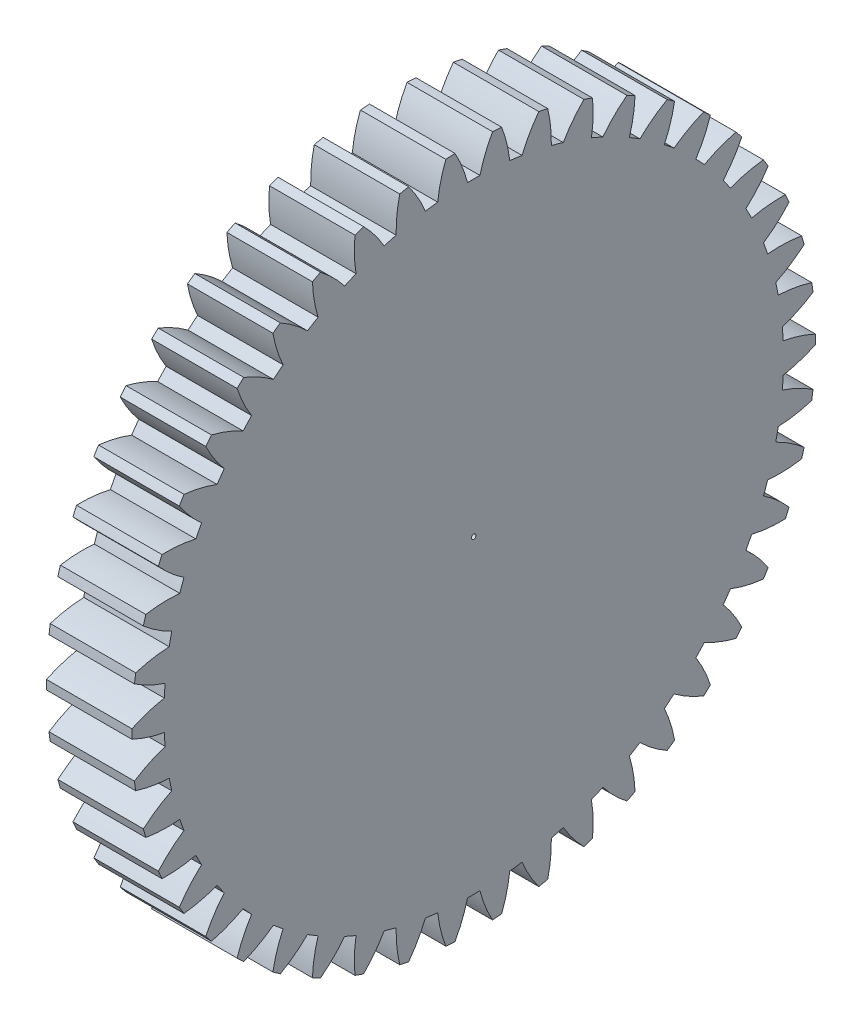
SolidWorks part; units mm, degrees
material "PLA "
ref_plane "Plane1" through (0, 0, 0) normal (0, 0, 1) x (1, 0, 0)
ref_plane "Plane2" through (0, 0, 0) normal (0, 1, 0) x (1, 0, 0)
ref_plane "Plane3" through (0, 0, 0) normal (1, 0, 0) x (0, 0, -1)
sketch "HoldingSke" plane through (0, 0, 0) normal (0, 1, 0) x (1, 0, 0)
  line L0 (0, 0) -> (0.2779, -0.2877)
  line L1 (-15, 0) -> (100, 0) construction
  line L2 (0, 0) -> (-2.1039, 2.3779)
  line L3 (0, 0) -> (-11.863, 4.5341)
  line L4 (0, 0) -> (5.9991, 6.2122)
  line L5 (0, 0) -> (-46.8476, -17.4728)
  line L6 (0, 0) -> (-9.9476, -6.7116)
  line L7 (-2.1039, 2.3779) -> (8.6586, 51.2059)
  line L8 (-76.2, 54.61) -> (-76.1, 54.61)
  line L9 (-71.009, 38.7566) -> (-53.1078, 45.2721)
  line L10 (-76.2, 71.12) -> (104.1128, 71.12)
  line L11 (0, 0) -> (-12, 0)
  line L12 (-76.2, 101.6) -> (-76.113, 101.6)
  line L13 (24.9733, 27.94) -> (52.9518, 28.4284)
  line L14 (24.9733, 27.94) -> (24.9743, 27.94)
  line L15 (24.9733, 27.94) -> (100.4006, 29.5858)
  line L16 (-63.627, -2.5) -> (-12.827, -2.5)
  circle A0 centre (0, 0) radius 0.4
  circle A1 centre (0, 0) radius 37.5
  circle A2 centre (0, 0) radius 37.5
  circle A3 centre (0, 0) radius 0.4
  dimension "MHD" = 75
  dimension "Hub_dia" = 75
  dimension "Bore" = 0.8
  dimension "MBD" = 0.8
  dimension "Num_teeth" = 46
  dimension "Pitch" = 0.4
  dimension "Overall_len" = 50
  dimension "Show_teeth" = 46
  dimension "Thickness" = 12
  dimension "OAL" = 50.0001
  dimension "T_dim" = 0.1
  dimension "Ap" = 20
  dimension "H" = 19.05
  dimension "Pitch_radius" = 180.3128
  dimension "Width" = 12
  dimension "Backlash" = 0.087
  dimension "Addendum_fac" = 1
  dimension "Dedendum_fac" = 1.25
  dimension "Clearance_fac" = 0.25
  dimension "Dedendum_add" = 0.001
  dimension "Module" = 2.5
sketch "BasProSke" plane through (0, 0, 0) normal (0, 1, 0) x (1, 0, 0)
  line L0 (-10, 0) -> (60, 0) construction
  line L1 (0, 0) -> (0, 60)
  line L2 (0, 0) -> (12, 0)
  line L3 (12, 0) -> (12, 60)
  line L4 (12, 60) -> (0, 60)
  dimension "Thickness" = 12
  dimension "Diameter" = 120
revolve "Base-Revolve" add sketch "BasProSke" angle 360 about L0
sketch "TooCutSke" plane through (0, 0, 0) normal (1, 0, 0) x (0, 0, -1)
  line L1 (0, 0) -> (0, 107) construction
  line L2 (0, 0) -> (-2.1154, 57.4611) construction
  line L3 (0, 0) -> (-7.844, 114.675) construction
  line L4 (-2.1154, 57.4611) -> (-3.922, 57.3375) construction
  arc A0 (1.091, 54.3631) -> (-1.091, 54.3631) centre (0, 0) ccw
  arc A1 (3.3102, 59.9341) -> (-3.3102, 59.9341) centre (0, 0) ccw
  circle A2 centre (0, 0) radius 57.5 construction
  circle A3 centre (0, 0) radius 54.0323 construction
  arc A4 (-1.091, 54.3631) -> (-3.3102, 59.9341) centre (-23.3853, 48.7095) ccw
  arc A5 (3.3102, 59.9341) -> (1.091, 54.3631) centre (23.3853, 48.7095) ccw
  dimension "Root_dia" = 108.748
  dimension "Overcut_dia" = 120.0508
  dimension "Pitch_dia" = 115
  dimension "Base_dia" = 108.0647
  dimension "Flank_rad" = 23
  dimension "Half_ang" = 3.913
  dimension "Half_CT" = 1.8109
extrude "ToothCut" cut sketch "TooCutSke" along normal through all
fillet "Breaks" [suppressed] radius 0.05
fillet "RootFillets" [suppressed] radius 0.626
pattern_circular "TeethCuts" count 46 over 360 about axis through (0, 0, 0) along (1, 0, 0) of "ToothCut", "RootFillets", "Breaks"
sketch "HubNeaOneSke" plane through (0, 0, 0) normal (-1, 0, 0) x (0, 0, 1)
  circle A0 centre (0, 0) radius 37.5
  dimension "Diameter" = 75
extrude "HubNearOne" [suppressed] add sketch "HubNeaOneSke" along normal blind 38.0001
sketch "HubNeaBotSke" plane through (0, 0, 0) normal (-1, 0, 0) x (0, 0, 1)
  circle A0 centre (0, 0) radius 37.5
  dimension "Diameter" = 75
extrude "HubNearBoth" [suppressed] add sketch "HubNeaBotSke" along normal blind 19
ref_plane "FarPln" through (12, 0, 0) normal (1, 0, 0) x (0, 0, -1)
sketch "HubFarSke" plane through (12, 0, 0) normal (1, 0, 0) x (0, 0, -1)
  circle A0 centre (0, 0) radius 37.5
  dimension "Diameter" = 75
extrude "HubFar" [suppressed] add sketch "HubFarSke" along normal blind 19
sketch "BorSke" plane through (0, 0, 0) normal (1, 0, 0) x (0, 0, -1)
  circle A0 centre (0, 0) radius 0.4
  dimension "Diameter" = 0.8
extrude "Bore" cut sketch "BorSke" along normal mid plane 100.0001
sketch "KeySke" plane through (0, 0, 0) normal (1, 0, 0) x (0, 0, -1)
  line L0 (-0.05, 0) -> (-0.05, 0.5)
  line L1 (-0.05, 0.5) -> (0.05, 0.5)
  line L2 (0.05, 0.5) -> (0.05, 0)
  line L3 (0, 0) -> (0, 34) construction
  line L4 (-0.05, 0) -> (0.05, 0)
  dimension "Offset" = 0.5
  dimension "Width" = 0.1
extrude "Keyway" [suppressed] cut sketch "KeySke" along normal mid plane 100.0001
pattern_circular "Keyway2" [suppressed] count 2 every 90 about axis through (-10, 0, 0) along (1, 0, 0)
sketch "Sketch1" plane through (12, 0, 0) normal (1, 0, 0) x (0, 0, -1)
  circle A0 centre (-0.4, 0) radius 22.4186
  circle A1 centre (0, 0) radius 0.4 construction
sketch "Sketch11" plane through (0, 0, 0) normal (0, 1, 0) x (1, 0, 0)
  circle A0 centre (12, 22.0186) radius 3.25
  dimension "D1" = 6.5
sketch "Sketch13" plane through (0, 0, 0) normal (-1, 0, 0) x (0, 0, 1)
  arc A184 (54.3108, -2.6215) -> (59.9947, -0.7996) centre (50.1919, 20.0067) ccw
  arc A185 (59.9947, -0.7996) -> (59.9947, 0.7996) centre (0, 0) ccw
  arc A186 (59.9947, 0.7996) -> (54.3108, 2.6215) centre (50.1919, -20.0067) ccw
  arc A187 (54.3108, 2.6215) -> (54.1619, 4.7983) centre (0, 0) ccw
  arc A188 (54.1619, 4.7983) -> (59.5448, 7.3771) centre (47.0001, 26.6548) ccw
  arc A189 (59.5448, 7.3771) -> (59.327, 8.9615) centre (0, 0) ccw
  arc A190 (59.327, 8.9615) -> (53.448, 9.9924) centre (52.4486, -12.9859) ccw
  arc A191 (53.448, 9.9924) -> (53.004, 12.1286) centre (0, 0) ccw
  arc A192 (53.004, 12.1286) -> (57.9856, 15.4164) centre (42.9329, 32.8064) ccw
  arc A193 (57.9856, 15.4164) -> (57.5542, 16.9564) centre (0, 0) ccw
  arc A194 (57.5542, 16.9564) -> (51.5895, 17.1771) centre (53.7284, -5.7232) ccw
  arc A195 (51.5895, 17.1771) -> (50.8588, 19.233) centre (0, 0) ccw
  arc A196 (50.8588, 19.233) -> (55.3464, 23.1685) centre (38.0658, 38.3469) ccw
  arc A197 (55.3464, 23.1685) -> (54.7092, 24.6354) centre (0, 0) ccw
  arc A198 (54.7092, 24.6354) -> (48.7701, 24.0419) centre (54.0072, 1.6461) ccw
  arc A199 (48.7701, 24.0419) -> (47.7662, 25.9792) centre (0, 0) ccw
  arc A200 (47.7662, 25.9792) -> (51.6761, 30.489) centre (32.4897, 43.173) ccw
  arc A201 (51.6761, 30.489) -> (50.8451, 31.8555) centre (0, 0) ccw
  arc A202 (50.8451, 31.8555) -> (45.0421, 30.4588) centre (53.2801, 8.9848) ccw
  arc A203 (45.0421, 30.4588) -> (43.7838, 32.2414) centre (0, 0) ccw
  arc A204 (43.7838, 32.2414) -> (47.0432, 37.2416) centre (26.3084, 47.1949) ccw
  arc A205 (47.0432, 37.2416) -> (46.0339, 38.4822) centre (0, 0) ccw
  arc A206 (46.0339, 38.4822) -> (40.4751, 36.3084) centre (51.5604, 16.156) ccw
  arc A207 (40.4751, 36.3084) -> (38.9858, 37.903) centre (0, 0) ccw
  arc A208 (38.9858, 37.903) -> (41.534, 43.3005) centre (19.637, 50.3377) ccw
  arc A209 (41.534, 43.3005) -> (40.3651, 44.3921) centre (0, 0) ccw
  arc A210 (40.3651, 44.3921) -> (35.1541, 41.4815) centre (48.8802, 23.0264) ccw
  arc A211 (35.1541, 41.4815) -> (33.4616, 42.8585) centre (0, 0) ccw
  arc A212 (33.4616, 42.8585) -> (35.251, 48.5527) centre (12.5998, 52.5427) ccw
  arc A213 (35.251, 48.5527) -> (33.9445, 49.475) centre (0, 0) ccw
  arc A214 (33.9445, 49.475) -> (29.1783, 45.882) centre (45.2896, 29.4678) ccw
  arc A215 (29.1783, 45.882) -> (27.314, 47.0157) centre (0, 0) ccw
  arc A216 (27.314, 47.0157) -> (28.3114, 52.9005) centre (5.3278, 53.769) ccw
  arc A217 (28.3114, 52.9005) -> (26.8915, 53.6363) centre (0, 0) ccw
  arc A218 (26.8915, 53.6363) -> (22.6589, 49.4278) centre (40.8552, 35.3602) ccw
  arc A219 (22.6589, 49.4278) -> (20.6577, 50.297) centre (0, 0) ccw
  arc A220 (20.6577, 50.297) -> (20.8445, 56.2629) centre (-2.0433, 53.9937) ccw
  arc A221 (20.8445, 56.2629) -> (19.3375, 56.7984) centre (0, 0) ccw
  arc A222 (19.3375, 56.7984) -> (15.7175, 52.0528) centre (35.6598, 40.594) ccw
  arc A223 (15.7175, 52.0528) -> (13.6165, 52.6415) centre (0, 0) ccw
  arc A224 (13.6165, 52.6415) -> (12.9892, 58.5771) centre (-9.3764, 53.2125) ccw
  arc A225 (12.9892, 58.5771) -> (11.4234, 58.9025) centre (0, 0) ccw
  arc A226 (11.4234, 58.9025) -> (8.4832, 53.7082) centre (29.8001, 45.0716) ccw
  arc A227 (8.4832, 53.7082) -> (6.3216, 54.0053) centre (0, 0) ccw
  arc A228 (6.3216, 54.0053) -> (4.892, 59.8002) centre (-16.5349, 51.4402) ccw
  arc A229 (4.892, 59.8002) -> (3.2964, 59.9094) centre (0, 0) ccw
  arc A230 (3.2964, 59.9094) -> (1.091, 54.3631) centre (23.3853, 48.7095) ccw
  arc A231 (1.091, 54.3631) -> (-1.091, 54.3631) centre (0, 0) ccw
  arc A232 (-1.091, 54.3631) -> (-3.2964, 59.9094) centre (-23.3853, 48.7095) ccw
  arc A233 (-3.2964, 59.9094) -> (-4.892, 59.8002) centre (0, 0) ccw
  arc A234 (-4.892, 59.8002) -> (-6.3216, 54.0053) centre (16.5349, 51.4402) ccw
  arc A235 (-6.3216, 54.0053) -> (-8.4832, 53.7082) centre (0, 0) ccw
  arc A236 (-8.4832, 53.7082) -> (-11.4234, 58.9025) centre (-29.8001, 45.0716) ccw
  arc A237 (-11.4234, 58.9025) -> (-12.9892, 58.5771) centre (0, 0) ccw
  arc A238 (-12.9892, 58.5771) -> (-13.6165, 52.6415) centre (9.3764, 53.2125) ccw
  arc A239 (-13.6165, 52.6415) -> (-15.7175, 52.0528) centre (0, 0) ccw
  arc A240 (-15.7175, 52.0528) -> (-19.3375, 56.7984) centre (-35.6598, 40.594) ccw
  arc A241 (-19.3375, 56.7984) -> (-20.8445, 56.2629) centre (0, 0) ccw
  arc A242 (-20.8445, 56.2629) -> (-20.6577, 50.297) centre (2.0433, 53.9937) ccw
  arc A243 (-20.6577, 50.297) -> (-22.6589, 49.4278) centre (0, 0) ccw
  arc A244 (-22.6589, 49.4278) -> (-26.8915, 53.6363) centre (-40.8552, 35.3602) ccw
  arc A245 (-26.8915, 53.6363) -> (-28.3114, 52.9005) centre (0, 0) ccw
  arc A246 (-28.3114, 52.9005) -> (-27.314, 47.0157) centre (-5.3278, 53.769) ccw
  arc A247 (-27.314, 47.0157) -> (-29.1783, 45.882) centre (0, 0) ccw
  arc A248 (-29.1783, 45.882) -> (-33.9445, 49.475) centre (-45.2896, 29.4678) ccw
  arc A249 (-33.9445, 49.475) -> (-35.251, 48.5527) centre (0, 0) ccw
  arc A250 (-35.251, 48.5527) -> (-33.4616, 42.8585) centre (-12.5998, 52.5427) ccw
  arc A251 (-33.4616, 42.8585) -> (-35.1541, 41.4815) centre (0, 0) ccw
  arc A252 (-35.1541, 41.4815) -> (-40.3651, 44.3921) centre (-48.8802, 23.0264) ccw
  arc A253 (-40.3651, 44.3921) -> (-41.534, 43.3005) centre (0, 0) ccw
  arc A254 (-41.534, 43.3005) -> (-38.9858, 37.903) centre (-19.637, 50.3377) ccw
  arc A255 (-38.9858, 37.903) -> (-40.4751, 36.3084) centre (0, 0) ccw
  arc A256 (-40.4751, 36.3084) -> (-46.0339, 38.4822) centre (-51.5604, 16.156) ccw
  arc A257 (-46.0339, 38.4822) -> (-47.0432, 37.2416) centre (0, 0) ccw
  arc A258 (-47.0432, 37.2416) -> (-43.7838, 32.2414) centre (-26.3084, 47.1949) ccw
  arc A259 (-43.7838, 32.2414) -> (-45.0421, 30.4588) centre (0, 0) ccw
  arc A260 (-45.0421, 30.4588) -> (-50.8451, 31.8555) centre (-53.2801, 8.9848) ccw
  arc A261 (-50.8451, 31.8555) -> (-51.6761, 30.489) centre (0, 0) ccw
  arc A262 (-51.6761, 30.489) -> (-47.7662, 25.9792) centre (-32.4897, 43.173) ccw
  arc A263 (-47.7662, 25.9792) -> (-48.7701, 24.0419) centre (0, 0) ccw
  arc A264 (-48.7701, 24.0419) -> (-54.7092, 24.6354) centre (-54.0072, 1.6461) ccw
  arc A265 (-54.7092, 24.6354) -> (-55.3464, 23.1685) centre (0, 0) ccw
  arc A266 (-55.3464, 23.1685) -> (-50.8588, 19.233) centre (-38.0658, 38.3469) ccw
  arc A267 (-50.8588, 19.233) -> (-51.5895, 17.1771) centre (0, 0) ccw
  arc A268 (-51.5895, 17.1771) -> (-57.5542, 16.9564) centre (-53.7284, -5.7232) ccw
  arc A269 (-57.5542, 16.9564) -> (-57.9856, 15.4164) centre (0, 0) ccw
  arc A270 (-57.9856, 15.4164) -> (-53.004, 12.1286) centre (-42.9329, 32.8064) ccw
  arc A271 (-53.004, 12.1286) -> (-53.448, 9.9924) centre (0, 0) ccw
  arc A272 (-53.448, 9.9924) -> (-59.327, 8.9615) centre (-52.4486, -12.9859) ccw
  arc A273 (-59.327, 8.9615) -> (-59.5448, 7.3771) centre (0, 0) ccw
  arc A274 (-59.5448, 7.3771) -> (-54.1619, 4.7983) centre (-47.0001, 26.6548) ccw
  arc A275 (-54.1619, 4.7983) -> (-54.3108, 2.6215) centre (0, 0) ccw
  arc A276 (-54.3108, 2.6215) -> (-59.9947, 0.7996) centre (-50.1919, -20.0067) ccw
  arc A277 (-59.9947, 0.7996) -> (-59.9947, -0.7996) centre (0, 0) ccw
  arc A278 (-59.9947, -0.7996) -> (-54.3108, -2.6215) centre (-50.1919, 20.0067) ccw
  arc A279 (-54.3108, -2.6215) -> (-54.1619, -4.7983) centre (0, 0) ccw
  arc A280 (-54.1619, -4.7983) -> (-59.5448, -7.3771) centre (-47.0001, -26.6548) ccw
  arc A281 (-59.5448, -7.3771) -> (-59.327, -8.9615) centre (0, 0) ccw
  arc A282 (-59.327, -8.9615) -> (-53.448, -9.9924) centre (-52.4486, 12.9859) ccw
  arc A283 (-53.448, -9.9924) -> (-53.004, -12.1286) centre (0, 0) ccw
  arc A284 (-53.004, -12.1286) -> (-57.9856, -15.4164) centre (-42.9329, -32.8064) ccw
  arc A285 (-57.9856, -15.4164) -> (-57.5542, -16.9564) centre (0, 0) ccw
  arc A286 (-57.5542, -16.9564) -> (-51.5895, -17.1771) centre (-53.7284, 5.7232) ccw
  arc A287 (-51.5895, -17.1771) -> (-50.8588, -19.233) centre (0, 0) ccw
  arc A288 (-50.8588, -19.233) -> (-55.3464, -23.1685) centre (-38.0658, -38.3469) ccw
  arc A289 (-55.3464, -23.1685) -> (-54.7092, -24.6354) centre (0, 0) ccw
  arc A290 (-54.7092, -24.6354) -> (-48.7701, -24.0419) centre (-54.0072, -1.6461) ccw
  arc A291 (-48.7701, -24.0419) -> (-47.7662, -25.9792) centre (0, 0) ccw
  arc A292 (-47.7662, -25.9792) -> (-51.6761, -30.489) centre (-32.4897, -43.173) ccw
  arc A293 (-51.6761, -30.489) -> (-50.8451, -31.8555) centre (0, 0) ccw
  arc A294 (-50.8451, -31.8555) -> (-45.0421, -30.4588) centre (-53.2801, -8.9848) ccw
  arc A295 (-45.0421, -30.4588) -> (-43.7838, -32.2414) centre (0, 0) ccw
  arc A296 (-43.7838, -32.2414) -> (-47.0432, -37.2416) centre (-26.3084, -47.1949) ccw
  arc A297 (-47.0432, -37.2416) -> (-46.0339, -38.4822) centre (0, 0) ccw
  arc A298 (-46.0339, -38.4822) -> (-40.4751, -36.3084) centre (-51.5604, -16.156) ccw
  arc A299 (-40.4751, -36.3084) -> (-38.9858, -37.903) centre (0, 0) ccw
  arc A300 (-38.9858, -37.903) -> (-41.534, -43.3005) centre (-19.637, -50.3377) ccw
  arc A301 (-41.534, -43.3005) -> (-40.3651, -44.3921) centre (0, 0) ccw
  arc A302 (-40.3651, -44.3921) -> (-35.1541, -41.4815) centre (-48.8802, -23.0264) ccw
  arc A303 (-35.1541, -41.4815) -> (-33.4616, -42.8585) centre (0, 0) ccw
  arc A304 (-33.4616, -42.8585) -> (-35.251, -48.5527) centre (-12.5998, -52.5427) ccw
  arc A305 (-35.251, -48.5527) -> (-33.9445, -49.475) centre (0, 0) ccw
  arc A306 (-33.9445, -49.475) -> (-29.1783, -45.882) centre (-45.2896, -29.4678) ccw
  arc A307 (-29.1783, -45.882) -> (-27.314, -47.0157) centre (0, 0) ccw
  arc A308 (-27.314, -47.0157) -> (-28.3114, -52.9005) centre (-5.3278, -53.769) ccw
  arc A309 (-28.3114, -52.9005) -> (-26.8915, -53.6363) centre (0, 0) ccw
  arc A310 (-26.8915, -53.6363) -> (-22.6589, -49.4278) centre (-40.8552, -35.3602) ccw
  arc A311 (-22.6589, -49.4278) -> (-20.6577, -50.297) centre (0, 0) ccw
  arc A312 (-20.6577, -50.297) -> (-20.8445, -56.2629) centre (2.0433, -53.9937) ccw
  arc A313 (-20.8445, -56.2629) -> (-19.3375, -56.7984) centre (0, 0) ccw
  arc A314 (-19.3375, -56.7984) -> (-15.7175, -52.0528) centre (-35.6598, -40.594) ccw
  arc A315 (-15.7175, -52.0528) -> (-13.6165, -52.6415) centre (0, 0) ccw
  arc A316 (-13.6165, -52.6415) -> (-12.9892, -58.5771) centre (9.3764, -53.2125) ccw
  arc A317 (-12.9892, -58.5771) -> (-11.4234, -58.9025) centre (0, 0) ccw
  arc A318 (-11.4234, -58.9025) -> (-8.4832, -53.7082) centre (-29.8001, -45.0716) ccw
  arc A319 (-8.4832, -53.7082) -> (-6.3216, -54.0053) centre (0, 0) ccw
  arc A320 (-6.3216, -54.0053) -> (-4.892, -59.8002) centre (16.5349, -51.4402) ccw
  arc A321 (-4.892, -59.8002) -> (-3.2964, -59.9094) centre (0, 0) ccw
  arc A322 (-3.2964, -59.9094) -> (-1.091, -54.3631) centre (-23.3853, -48.7095) ccw
  arc A323 (-1.091, -54.3631) -> (1.091, -54.3631) centre (0, 0) ccw
  arc A324 (1.091, -54.3631) -> (3.2964, -59.9094) centre (23.3853, -48.7095) ccw
  arc A325 (3.2964, -59.9094) -> (4.892, -59.8002) centre (0, 0) ccw
  arc A326 (4.892, -59.8002) -> (6.3216, -54.0053) centre (-16.5349, -51.4402) ccw
  arc A327 (6.3216, -54.0053) -> (8.4832, -53.7082) centre (0, 0) ccw
  arc A328 (8.4832, -53.7082) -> (11.4234, -58.9025) centre (29.8001, -45.0716) ccw
  arc A329 (11.4234, -58.9025) -> (12.9892, -58.5771) centre (0, 0) ccw
  arc A330 (12.9892, -58.5771) -> (13.6165, -52.6415) centre (-9.3764, -53.2125) ccw
  arc A331 (13.6165, -52.6415) -> (15.7175, -52.0528) centre (0, 0) ccw
  arc A332 (15.7175, -52.0528) -> (19.3375, -56.7984) centre (35.6598, -40.594) ccw
  arc A333 (19.3375, -56.7984) -> (20.8445, -56.2629) centre (0, 0) ccw
  arc A334 (20.8445, -56.2629) -> (20.6577, -50.297) centre (-2.0433, -53.9937) ccw
  arc A335 (20.6577, -50.297) -> (22.6589, -49.4278) centre (0, 0) ccw
  arc A336 (22.6589, -49.4278) -> (26.8915, -53.6363) centre (40.8552, -35.3602) ccw
  arc A337 (26.8915, -53.6363) -> (28.3114, -52.9005) centre (0, 0) ccw
  arc A338 (28.3114, -52.9005) -> (27.314, -47.0157) centre (5.3278, -53.769) ccw
  arc A339 (27.314, -47.0157) -> (29.1783, -45.882) centre (0, 0) ccw
  arc A340 (29.1783, -45.882) -> (33.9445, -49.475) centre (45.2896, -29.4678) ccw
  arc A341 (33.9445, -49.475) -> (35.251, -48.5527) centre (0, 0) ccw
  arc A342 (35.251, -48.5527) -> (33.4616, -42.8585) centre (12.5998, -52.5427) ccw
  arc A343 (33.4616, -42.8585) -> (35.1541, -41.4815) centre (0, 0) ccw
  arc A344 (35.1541, -41.4815) -> (40.3651, -44.3921) centre (48.8802, -23.0264) ccw
  arc A345 (40.3651, -44.3921) -> (41.534, -43.3005) centre (0, 0) ccw
  arc A346 (41.534, -43.3005) -> (38.9858, -37.903) centre (19.637, -50.3377) ccw
  arc A347 (38.9858, -37.903) -> (40.4751, -36.3084) centre (0, 0) ccw
  arc A348 (40.4751, -36.3084) -> (46.0339, -38.4822) centre (51.5604, -16.156) ccw
  arc A349 (46.0339, -38.4822) -> (47.0432, -37.2416) centre (0, 0) ccw
  arc A350 (47.0432, -37.2416) -> (43.7838, -32.2414) centre (26.3084, -47.1949) ccw
  arc A351 (43.7838, -32.2414) -> (45.0421, -30.4588) centre (0, 0) ccw
  arc A352 (45.0421, -30.4588) -> (50.8451, -31.8555) centre (53.2801, -8.9848) ccw
  arc A353 (50.8451, -31.8555) -> (51.6761, -30.489) centre (0, 0) ccw
  arc A354 (51.6761, -30.489) -> (47.7662, -25.9792) centre (32.4897, -43.173) ccw
  arc A355 (47.7662, -25.9792) -> (48.7701, -24.0419) centre (0, 0) ccw
  arc A356 (48.7701, -24.0419) -> (54.7092, -24.6354) centre (54.0072, -1.6461) ccw
  arc A357 (54.7092, -24.6354) -> (55.3464, -23.1685) centre (0, 0) ccw
  arc A358 (55.3464, -23.1685) -> (50.8588, -19.233) centre (38.0658, -38.3469) ccw
  arc A359 (50.8588, -19.233) -> (51.5895, -17.1771) centre (0, 0) ccw
  arc A360 (51.5895, -17.1771) -> (57.5542, -16.9564) centre (53.7284, 5.7232) ccw
  arc A361 (57.5542, -16.9564) -> (57.9856, -15.4164) centre (0, 0) ccw
  arc A362 (57.9856, -15.4164) -> (53.004, -12.1286) centre (42.9329, -32.8064) ccw
  arc A363 (53.004, -12.1286) -> (53.448, -9.9924) centre (0, 0) ccw
  arc A364 (53.448, -9.9924) -> (59.327, -8.9615) centre (52.4486, 12.9859) ccw
  arc A365 (59.327, -8.9615) -> (59.5448, -7.3771) centre (0, 0) ccw
  arc A366 (59.5448, -7.3771) -> (54.1619, -4.7983) centre (47.0001, -26.6548) ccw
  arc A367 (54.1619, -4.7983) -> (54.3108, -2.6215) centre (0, 0) ccw
  arc A368 (54.3108, -2.6215) -> (59.9947, -0.7996) centre (50.1919, 20.0067) ccw
  arc A369 (59.9947, -0.7996) -> (59.9947, 0.7996) centre (0, 0) ccw
  arc A370 (59.9947, 0.7996) -> (54.3108, 2.6215) centre (50.1919, -20.0067) ccw
  arc A371 (54.3108, 2.6215) -> (54.1619, 4.7983) centre (0, 0) ccw
  arc A372 (54.1619, 4.7983) -> (59.5448, 7.3771) centre (47.0001, 26.6548) ccw
  arc A373 (59.5448, 7.3771) -> (59.327, 8.9615) centre (0, 0) ccw
  arc A374 (59.327, 8.9615) -> (53.448, 9.9924) centre (52.4486, -12.9859) ccw
  arc A375 (53.448, 9.9924) -> (53.004, 12.1286) centre (0, 0) ccw
  arc A376 (53.004, 12.1286) -> (57.9856, 15.4164) centre (42.9329, 32.8064) ccw
  arc A377 (57.9856, 15.4164) -> (57.5542, 16.9564) centre (0, 0) ccw
  arc A378 (57.5542, 16.9564) -> (51.5895, 17.1771) centre (53.7284, -5.7232) ccw
  arc A379 (51.5895, 17.1771) -> (50.8588, 19.233) centre (0, 0) ccw
  arc A380 (50.8588, 19.233) -> (55.3464, 23.1685) centre (38.0658, 38.3469) ccw
  arc A381 (55.3464, 23.1685) -> (54.7092, 24.6354) centre (0, 0) ccw
  arc A382 (54.7092, 24.6354) -> (48.7701, 24.0419) centre (54.0072, 1.6461) ccw
  arc A383 (48.7701, 24.0419) -> (47.7662, 25.9792) centre (0, 0) ccw
  arc A384 (47.7662, 25.9792) -> (51.6761, 30.489) centre (32.4897, 43.173) ccw
  arc A385 (51.6761, 30.489) -> (50.8451, 31.8555) centre (0, 0) ccw
  arc A386 (50.8451, 31.8555) -> (45.0421, 30.4588) centre (53.2801, 8.9848) ccw
  arc A387 (45.0421, 30.4588) -> (43.7838, 32.2414) centre (0, 0) ccw
  arc A388 (43.7838, 32.2414) -> (47.0432, 37.2416) centre (26.3084, 47.1949) ccw
  arc A389 (47.0432, 37.2416) -> (46.0339, 38.4822) centre (0, 0) ccw
  arc A390 (46.0339, 38.4822) -> (40.4751, 36.3084) centre (51.5604, 16.156) ccw
  arc A391 (40.4751, 36.3084) -> (38.9858, 37.903) centre (0, 0) ccw
  arc A392 (38.9858, 37.903) -> (41.534, 43.3005) centre (19.637, 50.3377) ccw
  arc A393 (41.534, 43.3005) -> (40.3651, 44.3921) centre (0, 0) ccw
  arc A394 (40.3651, 44.3921) -> (35.1541, 41.4815) centre (48.8802, 23.0264) ccw
  arc A395 (35.1541, 41.4815) -> (33.4616, 42.8585) centre (0, 0) ccw
  arc A396 (33.4616, 42.8585) -> (35.251, 48.5527) centre (12.5998, 52.5427) ccw
  arc A397 (35.251, 48.5527) -> (33.9445, 49.475) centre (0, 0) ccw
  arc A398 (33.9445, 49.475) -> (29.1783, 45.882) centre (45.2896, 29.4678) ccw
  arc A399 (29.1783, 45.882) -> (27.314, 47.0157) centre (0, 0) ccw
  arc A400 (27.314, 47.0157) -> (28.3114, 52.9005) centre (5.3278, 53.769) ccw
  arc A401 (28.3114, 52.9005) -> (26.8915, 53.6363) centre (0, 0) ccw
  arc A402 (26.8915, 53.6363) -> (22.6589, 49.4278) centre (40.8552, 35.3602) ccw
  arc A403 (22.6589, 49.4278) -> (20.6577, 50.297) centre (0, 0) ccw
  arc A404 (20.6577, 50.297) -> (20.8445, 56.2629) centre (-2.0433, 53.9937) ccw
  arc A405 (20.8445, 56.2629) -> (19.3375, 56.7984) centre (0, 0) ccw
  arc A406 (19.3375, 56.7984) -> (15.7175, 52.0528) centre (35.6598, 40.594) ccw
  arc A407 (15.7175, 52.0528) -> (13.6165, 52.6415) centre (0, 0) ccw
  arc A408 (13.6165, 52.6415) -> (12.9892, 58.5771) centre (-9.3764, 53.2125) ccw
  arc A409 (12.9892, 58.5771) -> (11.4234, 58.9025) centre (0, 0) ccw
  arc A410 (11.4234, 58.9025) -> (8.4832, 53.7082) centre (29.8001, 45.0716) ccw
  arc A411 (8.4832, 53.7082) -> (6.3216, 54.0053) centre (0, 0) ccw
  arc A412 (6.3216, 54.0053) -> (4.892, 59.8002) centre (-16.5349, 51.4402) ccw
  arc A413 (4.892, 59.8002) -> (3.2964, 59.9094) centre (0, 0) ccw
  arc A414 (3.2964, 59.9094) -> (1.091, 54.3631) centre (23.3853, 48.7095) ccw
  arc A415 (1.091, 54.3631) -> (-1.091, 54.3631) centre (0, 0) ccw
  arc A416 (-1.091, 54.3631) -> (-3.2964, 59.9094) centre (-23.3853, 48.7095) ccw
  arc A417 (-3.2964, 59.9094) -> (-4.892, 59.8002) centre (0, 0) ccw
  arc A418 (-4.892, 59.8002) -> (-6.3216, 54.0053) centre (16.5349, 51.4402) ccw
  arc A419 (-6.3216, 54.0053) -> (-8.4832, 53.7082) centre (0, 0) ccw
  arc A420 (-8.4832, 53.7082) -> (-11.4234, 58.9025) centre (-29.8001, 45.0716) ccw
  arc A421 (-11.4234, 58.9025) -> (-12.9892, 58.5771) centre (0, 0) ccw
  arc A422 (-12.9892, 58.5771) -> (-13.6165, 52.6415) centre (9.3764, 53.2125) ccw
  arc A423 (-13.6165, 52.6415) -> (-15.7175, 52.0528) centre (0, 0) ccw
  arc A424 (-15.7175, 52.0528) -> (-19.3375, 56.7984) centre (-35.6598, 40.594) ccw
  arc A425 (-19.3375, 56.7984) -> (-20.8445, 56.2629) centre (0, 0) ccw
  arc A426 (-20.8445, 56.2629) -> (-20.6577, 50.297) centre (2.0433, 53.9937) ccw
  arc A427 (-20.6577, 50.297) -> (-22.6589, 49.4278) centre (0, 0) ccw
  arc A428 (-22.6589, 49.4278) -> (-26.8915, 53.6363) centre (-40.8552, 35.3602) ccw
  arc A429 (-26.8915, 53.6363) -> (-28.3114, 52.9005) centre (0, 0) ccw
  arc A430 (-28.3114, 52.9005) -> (-27.314, 47.0157) centre (-5.3278, 53.769) ccw
  arc A431 (-27.314, 47.0157) -> (-29.1783, 45.882) centre (0, 0) ccw
  arc A432 (-29.1783, 45.882) -> (-33.9445, 49.475) centre (-45.2896, 29.4678) ccw
  arc A433 (-33.9445, 49.475) -> (-35.251, 48.5527) centre (0, 0) ccw
  arc A434 (-35.251, 48.5527) -> (-33.4616, 42.8585) centre (-12.5998, 52.5427) ccw
  arc A435 (-33.4616, 42.8585) -> (-35.1541, 41.4815) centre (0, 0) ccw
  arc A436 (-35.1541, 41.4815) -> (-40.3651, 44.3921) centre (-48.8802, 23.0264) ccw
  arc A437 (-40.3651, 44.3921) -> (-41.534, 43.3005) centre (0, 0) ccw
  arc A438 (-41.534, 43.3005) -> (-38.9858, 37.903) centre (-19.637, 50.3377) ccw
  arc A439 (-38.9858, 37.903) -> (-40.4751, 36.3084) centre (0, 0) ccw
  arc A440 (-40.4751, 36.3084) -> (-46.0339, 38.4822) centre (-51.5604, 16.156) ccw
  arc A441 (-46.0339, 38.4822) -> (-47.0432, 37.2416) centre (0, 0) ccw
  arc A442 (-47.0432, 37.2416) -> (-43.7838, 32.2414) centre (-26.3084, 47.1949) ccw
  arc A443 (-43.7838, 32.2414) -> (-45.0421, 30.4588) centre (0, 0) ccw
  arc A444 (-45.0421, 30.4588) -> (-50.8451, 31.8555) centre (-53.2801, 8.9848) ccw
  arc A445 (-50.8451, 31.8555) -> (-51.6761, 30.489) centre (0, 0) ccw
  arc A446 (-51.6761, 30.489) -> (-47.7662, 25.9792) centre (-32.4897, 43.173) ccw
  arc A447 (-47.7662, 25.9792) -> (-48.7701, 24.0419) centre (0, 0) ccw
  arc A448 (-48.7701, 24.0419) -> (-54.7092, 24.6354) centre (-54.0072, 1.6461) ccw
  arc A449 (-54.7092, 24.6354) -> (-55.3464, 23.1685) centre (0, 0) ccw
  arc A450 (-55.3464, 23.1685) -> (-50.8588, 19.233) centre (-38.0658, 38.3469) ccw
  arc A451 (-50.8588, 19.233) -> (-51.5895, 17.1771) centre (0, 0) ccw
  arc A452 (-51.5895, 17.1771) -> (-57.5542, 16.9564) centre (-53.7284, -5.7232) ccw
  arc A453 (-57.5542, 16.9564) -> (-57.9856, 15.4164) centre (0, 0) ccw
  arc A454 (-57.9856, 15.4164) -> (-53.004, 12.1286) centre (-42.9329, 32.8064) ccw
  arc A455 (-53.004, 12.1286) -> (-53.448, 9.9924) centre (0, 0) ccw
  arc A456 (-53.448, 9.9924) -> (-59.327, 8.9615) centre (-52.4486, -12.9859) ccw
  arc A457 (-59.327, 8.9615) -> (-59.5448, 7.3771) centre (0, 0) ccw
  arc A458 (-59.5448, 7.3771) -> (-54.1619, 4.7983) centre (-47.0001, 26.6548) ccw
  arc A459 (-54.1619, 4.7983) -> (-54.3108, 2.6215) centre (0, 0) ccw
  arc A460 (-54.3108, 2.6215) -> (-59.9947, 0.7996) centre (-50.1919, -20.0067) ccw
  arc A461 (-59.9947, 0.7996) -> (-59.9947, -0.7996) centre (0, 0) ccw
  arc A462 (-59.9947, -0.7996) -> (-54.3108, -2.6215) centre (-50.1919, 20.0067) ccw
  arc A463 (-54.3108, -2.6215) -> (-54.1619, -4.7983) centre (0, 0) ccw
  arc A464 (-54.1619, -4.7983) -> (-59.5448, -7.3771) centre (-47.0001, -26.6548) ccw
  arc A465 (-59.5448, -7.3771) -> (-59.327, -8.9615) centre (0, 0) ccw
  arc A466 (-59.327, -8.9615) -> (-53.448, -9.9924) centre (-52.4486, 12.9859) ccw
  arc A467 (-53.448, -9.9924) -> (-53.004, -12.1286) centre (0, 0) ccw
  arc A468 (-53.004, -12.1286) -> (-57.9856, -15.4164) centre (-42.9329, -32.8064) ccw
  arc A469 (-57.9856, -15.4164) -> (-57.5542, -16.9564) centre (0, 0) ccw
  arc A470 (-57.5542, -16.9564) -> (-51.5895, -17.1771) centre (-53.7284, 5.7232) ccw
  arc A471 (-51.5895, -17.1771) -> (-50.8588, -19.233) centre (0, 0) ccw
  arc A472 (-50.8588, -19.233) -> (-55.3464, -23.1685) centre (-38.0658, -38.3469) ccw
  arc A473 (-55.3464, -23.1685) -> (-54.7092, -24.6354) centre (0, 0) ccw
  arc A474 (-54.7092, -24.6354) -> (-48.7701, -24.0419) centre (-54.0072, -1.6461) ccw
  arc A475 (-48.7701, -24.0419) -> (-47.7662, -25.9792) centre (0, 0) ccw
  arc A476 (-47.7662, -25.9792) -> (-51.6761, -30.489) centre (-32.4897, -43.173) ccw
  arc A477 (-51.6761, -30.489) -> (-50.8451, -31.8555) centre (0, 0) ccw
  arc A478 (-50.8451, -31.8555) -> (-45.0421, -30.4588) centre (-53.2801, -8.9848) ccw
  arc A479 (-45.0421, -30.4588) -> (-43.7838, -32.2414) centre (0, 0) ccw
  arc A480 (-43.7838, -32.2414) -> (-47.0432, -37.2416) centre (-26.3084, -47.1949) ccw
  arc A481 (-47.0432, -37.2416) -> (-46.0339, -38.4822) centre (0, 0) ccw
  arc A482 (-46.0339, -38.4822) -> (-40.4751, -36.3084) centre (-51.5604, -16.156) ccw
  arc A483 (-40.4751, -36.3084) -> (-38.9858, -37.903) centre (0, 0) ccw
  arc A484 (-38.9858, -37.903) -> (-41.534, -43.3005) centre (-19.637, -50.3377) ccw
  arc A485 (-41.534, -43.3005) -> (-40.3651, -44.3921) centre (0, 0) ccw
  arc A486 (-40.3651, -44.3921) -> (-35.1541, -41.4815) centre (-48.8802, -23.0264) ccw
  arc A487 (-35.1541, -41.4815) -> (-33.4616, -42.8585) centre (0, 0) ccw
  arc A488 (-33.4616, -42.8585) -> (-35.251, -48.5527) centre (-12.5998, -52.5427) ccw
  arc A489 (-35.251, -48.5527) -> (-33.9445, -49.475) centre (0, 0) ccw
  arc A490 (-33.9445, -49.475) -> (-29.1783, -45.882) centre (-45.2896, -29.4678) ccw
  arc A491 (-29.1783, -45.882) -> (-27.314, -47.0157) centre (0, 0) ccw
  arc A492 (-27.314, -47.0157) -> (-28.3114, -52.9005) centre (-5.3278, -53.769) ccw
  arc A493 (-28.3114, -52.9005) -> (-26.8915, -53.6363) centre (0, 0) ccw
  arc A494 (-26.8915, -53.6363) -> (-22.6589, -49.4278) centre (-40.8552, -35.3602) ccw
  arc A495 (-22.6589, -49.4278) -> (-20.6577, -50.297) centre (0, 0) ccw
  arc A496 (-20.6577, -50.297) -> (-20.8445, -56.2629) centre (2.0433, -53.9937) ccw
  arc A497 (-20.8445, -56.2629) -> (-19.3375, -56.7984) centre (0, 0) ccw
  arc A498 (-19.3375, -56.7984) -> (-15.7175, -52.0528) centre (-35.6598, -40.594) ccw
  arc A499 (-15.7175, -52.0528) -> (-13.6165, -52.6415) centre (0, 0) ccw
  arc A500 (-13.6165, -52.6415) -> (-12.9892, -58.5771) centre (9.3764, -53.2125) ccw
  arc A501 (-12.9892, -58.5771) -> (-11.4234, -58.9025) centre (0, 0) ccw
  arc A502 (-11.4234, -58.9025) -> (-8.4832, -53.7082) centre (-29.8001, -45.0716) ccw
  arc A503 (-8.4832, -53.7082) -> (-6.3216, -54.0053) centre (0, 0) ccw
  arc A504 (-6.3216, -54.0053) -> (-4.892, -59.8002) centre (16.5349, -51.4402) ccw
  arc A505 (-4.892, -59.8002) -> (-3.2964, -59.9094) centre (0, 0) ccw
  arc A506 (-3.2964, -59.9094) -> (-1.091, -54.3631) centre (-23.3853, -48.7095) ccw
  arc A507 (-1.091, -54.3631) -> (1.091, -54.3631) centre (0, 0) ccw
  arc A508 (1.091, -54.3631) -> (3.2964, -59.9094) centre (23.3853, -48.7095) ccw
  arc A509 (3.2964, -59.9094) -> (4.892, -59.8002) centre (0, 0) ccw
  arc A510 (4.892, -59.8002) -> (6.3216, -54.0053) centre (-16.5349, -51.4402) ccw
  arc A511 (6.3216, -54.0053) -> (8.4832, -53.7082) centre (0, 0) ccw
  arc A512 (8.4832, -53.7082) -> (11.4234, -58.9025) centre (29.8001, -45.0716) ccw
  arc A513 (11.4234, -58.9025) -> (12.9892, -58.5771) centre (0, 0) ccw
  arc A514 (12.9892, -58.5771) -> (13.6165, -52.6415) centre (-9.3764, -53.2125) ccw
  arc A515 (13.6165, -52.6415) -> (15.7175, -52.0528) centre (0, 0) ccw
  arc A516 (15.7175, -52.0528) -> (19.3375, -56.7984) centre (35.6598, -40.594) ccw
  arc A517 (19.3375, -56.7984) -> (20.8445, -56.2629) centre (0, 0) ccw
  arc A518 (20.8445, -56.2629) -> (20.6577, -50.297) centre (-2.0433, -53.9937) ccw
  arc A519 (20.6577, -50.297) -> (22.6589, -49.4278) centre (0, 0) ccw
  arc A520 (22.6589, -49.4278) -> (26.8915, -53.6363) centre (40.8552, -35.3602) ccw
  arc A521 (26.8915, -53.6363) -> (28.3114, -52.9005) centre (0, 0) ccw
  arc A522 (28.3114, -52.9005) -> (27.314, -47.0157) centre (5.3278, -53.769) ccw
  arc A523 (27.314, -47.0157) -> (29.1783, -45.882) centre (0, 0) ccw
  arc A524 (29.1783, -45.882) -> (33.9445, -49.475) centre (45.2896, -29.4678) ccw
  arc A525 (33.9445, -49.475) -> (35.251, -48.5527) centre (0, 0) ccw
  arc A526 (35.251, -48.5527) -> (33.4616, -42.8585) centre (12.5998, -52.5427) ccw
  arc A527 (33.4616, -42.8585) -> (35.1541, -41.4815) centre (0, 0) ccw
  arc A528 (35.1541, -41.4815) -> (40.3651, -44.3921) centre (48.8802, -23.0264) ccw
  arc A529 (40.3651, -44.3921) -> (41.534, -43.3005) centre (0, 0) ccw
  arc A530 (41.534, -43.3005) -> (38.9858, -37.903) centre (19.637, -50.3377) ccw
  arc A531 (38.9858, -37.903) -> (40.4751, -36.3084) centre (0, 0) ccw
  arc A532 (40.4751, -36.3084) -> (46.0339, -38.4822) centre (51.5604, -16.156) ccw
  arc A533 (46.0339, -38.4822) -> (47.0432, -37.2416) centre (0, 0) ccw
  arc A534 (47.0432, -37.2416) -> (43.7838, -32.2414) centre (26.3084, -47.1949) ccw
  arc A535 (43.7838, -32.2414) -> (45.0421, -30.4588) centre (0, 0) ccw
  arc A536 (45.0421, -30.4588) -> (50.8451, -31.8555) centre (53.2801, -8.9848) ccw
  arc A537 (50.8451, -31.8555) -> (51.6761, -30.489) centre (0, 0) ccw
  arc A538 (51.6761, -30.489) -> (47.7662, -25.9792) centre (32.4897, -43.173) ccw
  arc A539 (47.7662, -25.9792) -> (48.7701, -24.0419) centre (0, 0) ccw
  arc A540 (48.7701, -24.0419) -> (54.7092, -24.6354) centre (54.0072, -1.6461) ccw
  arc A541 (54.7092, -24.6354) -> (55.3464, -23.1685) centre (0, 0) ccw
  arc A542 (55.3464, -23.1685) -> (50.8588, -19.233) centre (38.0658, -38.3469) ccw
  arc A543 (50.8588, -19.233) -> (51.5895, -17.1771) centre (0, 0) ccw
  arc A544 (51.5895, -17.1771) -> (57.5542, -16.9564) centre (53.7284, 5.7232) ccw
  arc A545 (57.5542, -16.9564) -> (57.9856, -15.4164) centre (0, 0) ccw
  arc A546 (57.9856, -15.4164) -> (53.004, -12.1286) centre (42.9329, -32.8064) ccw
  arc A547 (53.004, -12.1286) -> (53.448, -9.9924) centre (0, 0) ccw
  arc A548 (53.448, -9.9924) -> (59.327, -8.9615) centre (52.4486, 12.9859) ccw
  arc A549 (59.327, -8.9615) -> (59.5448, -7.3771) centre (0, 0) ccw
  arc A550 (59.5448, -7.3771) -> (54.1619, -4.7983) centre (47.0001, -26.6548) ccw
  arc A551 (54.1619, -4.7983) -> (54.3108, -2.6215) centre (0, 0) ccw
  dimension "D1" = 0
extrude "Boss-Extrude1" add sketch "Sketch13" along normal blind 3
equation "' \"Module@HoldingSke\" = 6.35"
equation "' \"Num_teeth@HoldingSke\" = 12"
equation "' \"Ap@HoldingSke\" =  20"
equation "' \"Ap@HoldingSke\" = 20"
equation "' \"Width@HoldingSke\" = 0.5 * 25.4"
equation "' \"Hub_dia@HoldingSke\"= 1 * 25.4"
equation "' \"Hub_dia@HoldingSke\" = 1 * 25.4"
equation "' \"Overall_len@HoldingSke\" = 1.0 * 25.4"
equation "' \"Bore@HoldingSke\" = 0.75 * 25.4"
equation "' \"T_dim@HoldingSke\" = 0.1 * 25.4"
equation "' \"Width@KeySke\" = 0.25 * 25.4"
equation "' \"Show_teeth@HoldingSke\" = 13"
equation "' \"Backlash@HoldingSke\" = 0.009 * 25.4"
equation "' \"Addendum_fac@HoldingSke\" = 1.0"
equation "' \"Dedendum_fac@HoldingSke\" = 1.25"
equation "' \"Dedendum_add@HoldingSke\" = 0.00005 * 25.4"
equation "' \"Clearance_fac@HoldingSke\" = 0.25"
equation "\"Pitch@HoldingSke\" = 1 / \"Module@HoldingSke\""
equation "\"Overcut_dia@TooCutSke\" = (\"Num_teeth@HoldingSke\" + 2 * \"Addendum_fac@HoldingSke\") / \"Pitch@HoldingSke\" + 0.002 * 25.4"
equation "\"Pitch_dia@TooCutSke\" = \"Num_teeth@HoldingSke\" / \"Pitch@HoldingSke\""
equation "\"Base_dia@TooCutSke\" = \"Num_teeth@HoldingSke\" / \"Pitch@HoldingSke\" * cos((\"Ap@HoldingSke\"  * 3.14159265 / 180))"
equation "\"Root_dia@TooCutSke\" = (\"Num_teeth@HoldingSke\" + 2) / \"Pitch@HoldingSke\" - 2 * (\"Addendum_fac@HoldingSke\" + \"Dedendum_fac@HoldingSke\") / \"Pitch@HoldingSke\" - \"Dedendum_add@HoldingSke\" * 2"
equation "\"Half_ang@TooCutSke\" = 180 / \"Num_teeth@HoldingSke\""
equation "\"Half_CT@TooCutSke\" = \"Num_teeth@HoldingSke\" / \"Pitch@HoldingSke\" * sin((3.14159265 / 2 / \"Num_teeth@HoldingSke\")) / 2 - 7 * \"Backlash@HoldingSke\" / 4"
equation "\"Flank_rad@TooCutSke\" = \"Num_teeth@HoldingSke\" / \"Pitch@HoldingSke\" / 5"
equation "\"Radius@RootFillets\" = \"Clearance_fac@HoldingSke\" / \"Pitch@HoldingSke\" + \"Dedendum_add@HoldingSke\""
equation "\"Break_rad@Breaks\" = 0.02 / \"Pitch@HoldingSke\""
equation "\"Thickness@HoldingSke\" = \"Width@HoldingSke\""
equation "\"OAL@HoldingSke\" = \"Thickness@HoldingSke\""
equation "\"MHD@HoldingSke\" = (\"Num_teeth@HoldingSke\" + 2) / \"Pitch@HoldingSke\" - 2 * (\"Addendum_fac@HoldingSke\" + \"Dedendum_fac@HoldingSke\")  / \"Pitch@HoldingSke\" - \"Dedendum_add@HoldingSke\" * 2"
equation "\"MBD@HoldingSke\" = (\"Num_teeth@HoldingSke\" + 2) / \"Pitch@HoldingSke\" - 2 * (\"Addendum_fac@HoldingSke\" + \"Dedendum_fac@HoldingSke\")  / \"Pitch@HoldingSke\" - \"Dedendum_add@HoldingSke\" * 2 - 0.002 * 25.4"
equation "\"MHD@HoldingSke\" = ((sgn( \"MHD@HoldingSke\" - \"Hub_dia@HoldingSke\" )-1)*( \"MHD@HoldingSke\" - \"Hub_dia@HoldingSke\" ))/-2+ \"Hub_dia@HoldingSke\""
equation "\"MBD@HoldingSke\" = ((sgn( \"MBD@HoldingSke\" - \"Bore@HoldingSke\" )-1)*( \"MBD@HoldingSke\" - \"Bore@HoldingSke\" ))/-2+ \"Bore@HoldingSke\""
equation "\"OAL@HoldingSke\" = ((sgn( \"OAL@HoldingSke\" - \"Overall_len@HoldingSke\" )+1)*( \"OAL@HoldingSke\" - \"Overall_len@HoldingSke\" ))/2 + \"Overall_len@HoldingSke\" + 0.000002 * 25.4"
equation "\"Num_teeth@TeethCuts\" = int( \"Show_teeth@HoldingSke\" ) + 1"
equation "\"Num_teeth@TeethCuts\" = ((sgn( \"Num_teeth@TeethCuts\" - \"Num_teeth@HoldingSke\" )-1)*( \"Num_teeth@TeethCuts\" - \"Num_teeth@HoldingSke\" ))/-2+ \"Num_teeth@HoldingSke\""
equation "\"Num_teeth@TeethCuts\" = ((sgn( \"Num_teeth@TeethCuts\" - 2.0)+1)*( \"Num_teeth@TeethCuts\" - 2.0))/2 +2.0"
equation "\"Angle@TeethCuts\" = 360.0 / \"Num_teeth@HoldingSke\""
equation "\"Diameter@BasProSke\" = (\"Num_teeth@HoldingSke\" + 2 * \"Addendum_fac@HoldingSke\") / \"Pitch@HoldingSke\""
equation "\"Thickness@BasProSke\"  = \"Thickness@HoldingSke\""
equation "' \"Fillet_rad@BasProSke\" =  \"Thickness@HoldingSke\" * 0.05"
equation "' \"Fillet_rad@BasProSke\" = \"Thickness@HoldingSke\" * 0.05"
equation "\"MHD@HoldingSke\" = ((sgn( \"MHD@HoldingSke\" - \"Root_dia@TooCutSke\" )-1)*( \"MHD@HoldingSke\" - \"Root_dia@TooCutSke\" ))/-2+ \"Root_dia@TooCutSke\""
equation "\"Diameter@HubNeaOneSke\" = \"MHD@HoldingSke\""
equation "\"Length@HubNearOne\" = \"OAL@HoldingSke\" - \"Thickness@BasProSke\""
equation "\"Diameter@HubNeaBotSke\" = \"MHD@HoldingSke\""
equation "\"Length@HubNearBoth\" = ( \"OAL@HoldingSke\" - \"Thickness@BasProSke\" ) / 2.0"
equation "\"Thickness@FarPln\" = \"Thickness@BasProSke\""
equation "\"Diameter@HubFarSke\" = \"MHD@HoldingSke\""
equation "\"Length@HubFar\" = ( \"OAL@HoldingSke\" - \"Thickness@BasProSke\" ) / 2.0"
equation "\"Diameter@BorSke\" = \"MBD@HoldingSke\""
equation "\"D1@Bore\" = \"OAL@HoldingSke\" * 2.0"
equation "\"D1@Keyway\" = \"OAL@HoldingSke\" * 2.0"
equation "\"Offset@KeySke\" = \"T_dim@HoldingSke\" + \"MBD@HoldingSke\" / 2.0"
